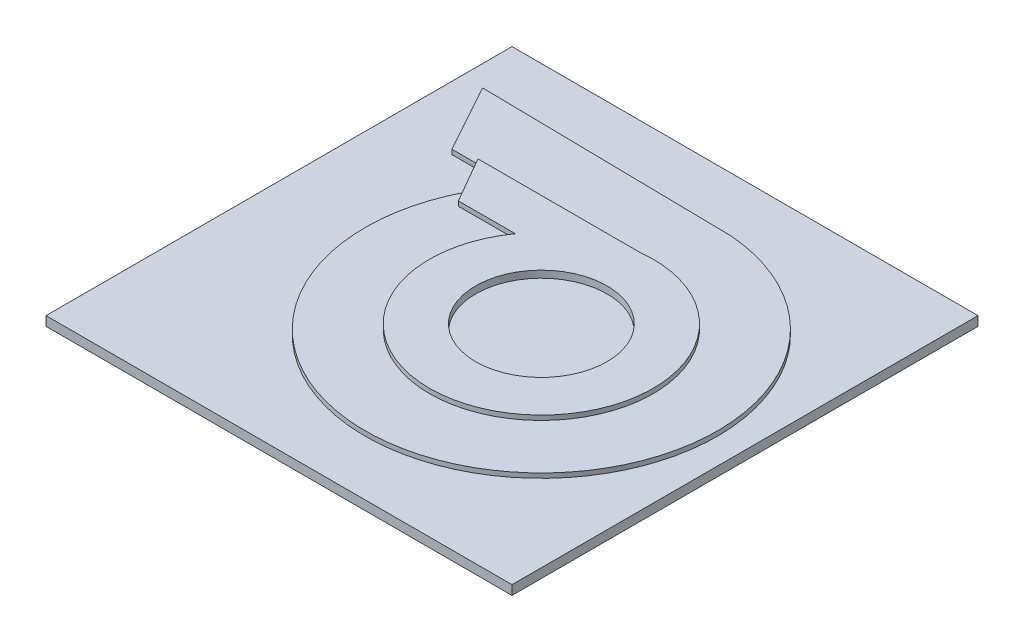
SolidWorks part; units mm, degrees
ref_plane "Front Plane" through (0, 0, 0) normal (0, 0, 1) x (1, 0, 0)
ref_plane "Top Plane" through (0, 0, 0) normal (0, 1, 0) x (1, 0, 0)
ref_plane "Right Plane" through (0, 0, 0) normal (1, 0, 0) x (0, 0, -1)
sketch "Sketch1" plane through (0, 0, 0) normal (0, 1, 0) x (1, 0, 0)
  line L1 (-50, 50) -> (50, 50)
  line L2 (-50, 50) -> (-50, -50)
  line L3 (-50, -50) -> (50, -50)
  line L4 (50, 50) -> (50, -50)
  line L5 (-50, 50) -> (50, -50) construction
  line L6 (-50, -50) -> (50, 50) construction
  point P4 (0, 0)
  dimension "D1" = 100
extrude "Boss-Extrude1" add sketch "Sketch1" along normal blind 2
sketch "Sketch2" plane through (0, 2, 0) normal (0, 1, 0) x (1, 0, 0)
  line L1 (-50, 50) -> (50, 50) construction
  line L2 (-50, 50) -> (-50, -50) construction
  line L3 (-50, -50) -> (50, -50) construction
  line L4 (50, 50) -> (50, -50) construction
  line L5 (-50, 50) -> (50, -50) construction
  line L6 (-50, -50) -> (50, 50) construction
  point P4 (0, 0)
sketch "Inner Lines Incorrect" plane through (0, 2, 0) normal (0, 1, 0) x (-1, 0, 0)
  line L0 (-37.8168, 47.4338) -> (112.1832, 47.4338) construction
  line L7 (6.6658, -38.1625) -> (44.4637, -38.1625) construction
  line L8 (44.4637, -38.1625) -> (44.4637, -0.3647) construction
  line L9 (44.4637, -38.1625) -> (-44.4637, 38.1625) construction
  point P4 (0, 0)
  line B0 (44.4637, -38.1625) -> (-9.7407, -37.308)
  line B1 (44.4637, -38.1625) -> (36.373, -23.4795)
  line B2 (36.373, -23.4795) -> (22.6623, -23.4795)
  line B3 (30.8341, -23.5717) -> (25.1132, -13.6355)
  line B4 (25.1132, -13.6355) -> (12.9402, -13.6355)
  line B5 (30.8341, -23.5717) -> (-6.4665, -23.726)
  circle B6 centre (-5.773, 0.6501) radius 14.1023
  arc B7 (22.6623, -23.4795) -> (-9.7407, -37.308) centre (-6.6658, 0.3647) ccw
  arc B8 (12.9402, -13.6355) -> (-6.4665, -23.726) centre (-6.6658, 0.3647) ccw
sketch_block_instance "Block1-1"
sketch_block "Block1"
extrude "Boss-Extrude2" add sketch "Inner Lines Incorrect" along normal blind 1 contours B0 B7 B2 B1 | B4 B8 B5 B3
sketch "Perfect Trace FT Logo" plane through (0, 3, 0) normal (0, 1, 0) x (-1, 0, 0)
  line L6 (44.4967, -38.1625) -> (-9.7428, -37.3335)
  line L7 (44.4967, -38.1625) -> (36.406, -23.4795)
  line L8 (36.406, -23.4795) -> (22.6953, -23.4795)
  line L9 (30.781, -23.4795) -> (25.0717, -13.5634)
  line L10 (25.0717, -13.5634) -> (12.8657, -13.5823)
  line L11 (30.781, -23.4795) -> (-3.935, -23.4795)
  line L14 (30.781, -23.4795) -> (26.9748, -16.8687) construction
  line L15 (36.373, -23.4795) -> (30.781, -23.4795) construction
  arc A3 (26.9748, -16.8687) -> (-9.7407, -37.308) centre (-6.6658, 0.3647) ccw construction
  arc A4 (26.9748, -16.8687) -> (-9.7407, -37.308) centre (-6.6658, 0.3647) ccw construction
  circle A5 centre (-6.6658, 0.3647) radius 14.1023
  arc A6 (22.6953, -23.4795) -> (-9.7428, -37.3335) centre (-6.6658, 0.3647) ccw
  arc A7 (12.8657, -13.5823) -> (-3.935, -23.4795) centre (-6.6658, 0.3647) ccw
  point P0 (0, 0)
  dimension "D1" = 24
extrude "Boss-Extrude5" add sketch "Perfect Trace FT Logo" along normal blind 1 contours L11 A7 L10 L9
sketch "Sketch10" plane through (0, 4, 0) normal (0, 1, 0) x (1, 0, 0)
  line L3 (-30.781, 23.4795) -> (-25.0717, 13.5634)
  line L4 (-25.0717, 13.5634) -> (-12.8657, 13.5823)
  line L5 (3.935, 23.4795) -> (-30.781, 23.4795)
  line L6 (-30.781, 23.4795) -> (-25.0717, 13.5634) construction
  line L7 (-25.0717, 13.5634) -> (-12.8657, 13.5823) construction
  line L8 (3.935, 23.4795) -> (-30.781, 23.4795) construction
  line L9 (9.7428, 37.3335) -> (-44.4967, 38.1625)
  line L10 (-36.406, 23.4795) -> (-22.6953, 23.4795)
  line L11 (-44.4967, 38.1625) -> (-36.406, 23.4795)
  line L12 (9.7428, 37.3335) -> (-44.4967, 38.1625) construction
  line L13 (-36.406, 23.4795) -> (-22.6953, 23.4795) construction
  line L14 (-44.4967, 38.1625) -> (-36.406, 23.4795) construction
  circle A1 centre (6.6658, -0.3647) radius 14.1023
  circle A2 centre (6.6658, -0.3647) radius 14.1023
  arc A3 (-12.8657, 13.5823) -> (3.935, 23.4795) centre (6.6658, -0.3647) ccw
  arc A4 (-12.8657, 13.5823) -> (3.935, 23.4795) centre (6.6658, -0.3647) ccw construction
  arc A5 (-22.6953, 23.4795) -> (9.7428, 37.3335) centre (6.6658, -0.3647) ccw
  arc A6 (-22.6953, 23.4795) -> (9.7428, 37.3335) centre (6.6658, -0.3647) ccw construction
  dimension "D1" = 0
  dimension "D2" = 0
  dimension "D3" = 0
extrude "Cut-Extrude1" cut sketch "Sketch10" against normal blind 1.5 contours A2
